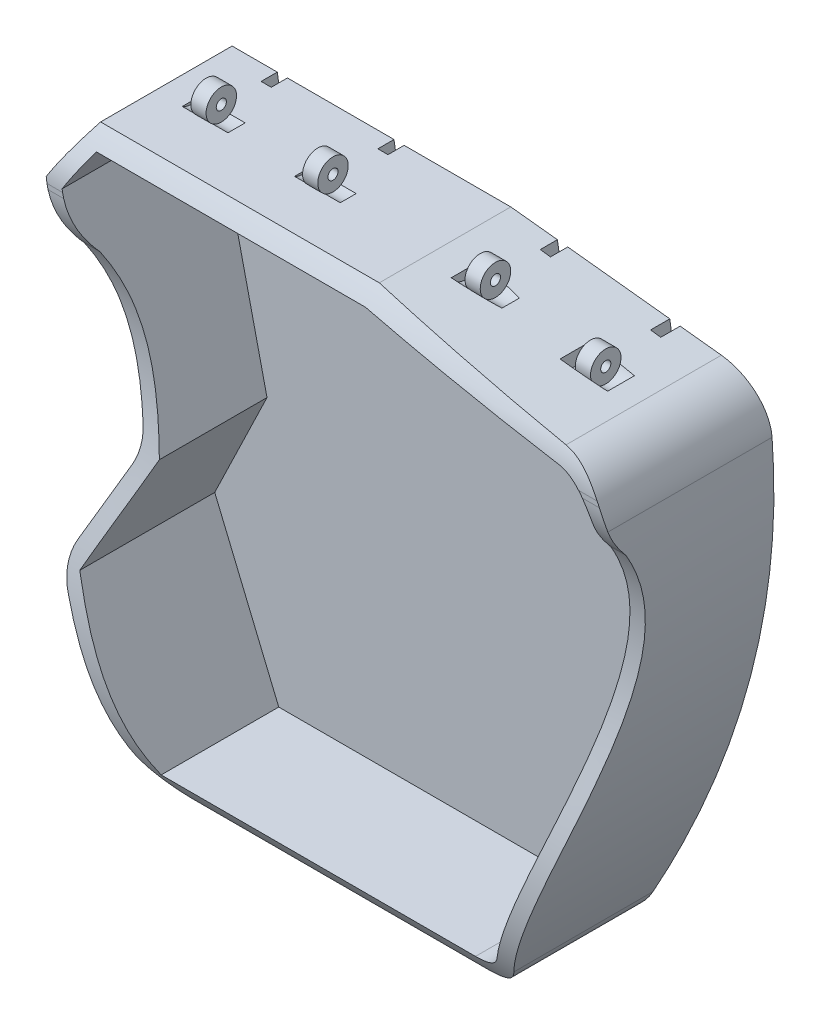
SolidWorks part; units mm, degrees
ref_plane "Front Plane" through (0, 0, 0) normal (0, 0, 1) x (1, 0, 0)
ref_plane "Top Plane" through (0, 0, 0) normal (0, 1, 0) x (1, 0, 0)
ref_plane "Right Plane" through (0, 0, 0) normal (1, 0, 0) x (0, 0, -1)
sketch "Sketch1" plane through (0, 0, 0) normal (0, 0, 1) x (1, 0, 0)
  line L1 (-55, -55) -> (55, -55)
  line L2 (-55, -55) -> (-55, 55)
  line L3 (-55, 55) -> (55, 55)
  line L4 (55, -55) -> (55, 55)
  line L5 (-55, -55) -> (55, 55) construction
  line L6 (-55, 55) -> (55, -55) construction
  point P0 (0, 0)
  dimension "D1" = 110
  dimension "D2" = 110
extrude "Boss-Extrude1" add sketch "Sketch1" along normal mid plane 40
sketch "Sketch2" plane through (0, 0, 20) normal (0, 0, 1) x (1, 0, 0)
  line L0 (-41.1067, -55) -> (-55, -21.5906)
  line L1 (-55, 55) -> (-55, -55) construction
  line L2 (55, 55) -> (-55, 55) construction
  line L3 (-44.5757, 55) -> (5.4243, 55)
  line L4 (-55, -21.5906) -> (-44.5757, 0)
  line L5 (-44.5757, 0) -> (-55, 45.5267)
  line L6 (55, -55) -> (55, 55) construction
  line L7 (-55, -55) -> (55, -55) construction
  line L8 (-44.5757, 55) -> (-49.4797, 55)
  line L9 (-49.4797, 55) -> (-55, 45.5267)
  line L10 (5.4243, 55) -> (55, 48.5)
  spline S0 degree 2 poles (55, 48.5) (55, -6.4605) (28.8836, -55) knots 0 0 0 1 1 1
  point P19 (-41.1067, 5.6448)
  point P20 (-55, 0)
  dimension "D6" = 50
  dimension "D3" = 50
  dimension "D4" = 6.5
extrude "Cut-Extrude1" cut sketch "Sketch2" against normal through all both and the other way through all
ref_plane "Plane1" through (0, 0, -20) normal (0, 0, 1) x (1, 0, 0)
fillet "Fillet1" radius 10 2 edges at (28.8836, -55, 0) (55, 48.5, 0)
sketch "Sketch34" plane through (0, 0, 20) normal (0, 0, 1) x (1, 0, 0)
  line L14 (-39.1052, -52) -> (22.8183, -52)
  line L15 (45.7352, 46.6891) -> (5.2285, 52)
  line L16 (5.2285, 52) -> (-47.7557, 52)
  line L17 (-47.7557, 52) -> (-51.8111, 45.0406)
  line L18 (-51.8111, 45.0406) -> (-41.4164, -0.3565)
  line L19 (-41.4164, -0.3565) -> (-51.7129, -21.6822)
  line L20 (-51.7129, -21.6822) -> (-39.1052, -52)
  line L21 (-39.1052, -52) -> (22.8183, -52)
  line L22 (45.7352, 46.6891) -> (5.2285, 52)
  line L23 (5.2285, 52) -> (-47.7557, 52)
  line L24 (-47.7557, 52) -> (-51.8111, 45.0406)
  line L25 (-51.8111, 45.0406) -> (-41.4164, -0.3565)
  line L26 (-41.4164, -0.3565) -> (-51.7129, -21.6822)
  line L27 (-51.7129, -21.6822) -> (-39.1052, -52)
  arc A4 (22.8183, -52) -> (29.0695, -48.15) centre (22.8183, -45) ccw
  arc A5 (51.8196, 39.4676) -> (45.7352, 46.6891) centre (44.8252, 39.7485) ccw
  arc A6 (22.8183, -52) -> (29.0695, -48.15) centre (22.8183, -45) ccw
  arc A7 (51.8196, 39.4676) -> (45.7352, 46.6891) centre (44.8252, 39.7485) ccw
  spline S0 degree 3 poles (-3904.7286, -573.1485) (-2467.861, -421.0759) (-98.4263, -556.5702) (47.0636, 1.6142) (48.5776, 9.0491) (49.9702, 18.497) (50.224, 20.3961) (50.68, 24.1989) (50.8823, 26.1025) (105.7114, 616.4777) (-2256.861, 1408.0002) (2334.2829, 1615.3931) knots -18.329353 -18.329353 -18.329353 -18.329353 0.5 0.5 0.75 0.75 0.8125 0.8125 0.875 0.875 20.174807 20.174807 20.174807 20.174807 only from (29.0695, -48.15) to (51.8196, 39.4676)
  spline S1 degree 3 poles (29.0695, -48.15) (35.9622, -34.4718) (41.3444, -20.3278) (47.0636, 1.6142) (48.5776, 9.0491) (49.9702, 18.497) (50.224, 20.3961) (50.68, 24.1989) (51.287, 29.9096) (51.6658, 35.6394) (51.8196, 39.4676) knots 0 0 0 0 0.5 0.5 0.75 0.75 0.8125 0.8125 0.875 1 1 1 1
  dimension "D1" = 3
extrude "Cut-Extrude18" cut sketch "Sketch34" against normal blind 30
sketch "Sketch3" plane through (0, 0, 0) normal (1, 0, 0) x (0, 0, -1)
  line L0 (9.8258, 63.2681) -> (27.0619, 63.2681)
  line L1 (27.0619, 63.2681) -> (27.0619, -62.3212)
  line L2 (27.0619, -62.3212) -> (11.0995, -62.3212)
  line L4 (-14.7201, 55) -> (-14.7201, 63.2681)
  line L5 (-14.7201, 63.2681) -> (-35.1683, 63.2681)
  line L6 (-35.1683, 63.2681) -> (-35.1683, -64.091)
  line L7 (-35.1683, -64.091) -> (-1.2006, -64.091)
  line L8 (-1.2006, -64.091) -> (-10.8074, -55.445)
  line L12 (-20, 55) -> (20, 55) construction
  line L13 (-20, 49.6636) -> (-20, 39.3472) construction
  spline S0 degree 2 poles (9.8258, 63.2681) (20.8245, 0.5714) (11.0995, -62.3212) knots 0 0 0 1 1 1
  spline S1 degree 2 poles (-14.7201, 55) (-25.0524, 44.4525) (-15.2012, 33.2765) knots 0 0 0 1 1 1
  spline S2 degree 3 poles (-15.2012, 33.2765) (3.7139, 2.8075) (-32.6776, -26.7515) (-10.8074, -55.445) knots 0 0 0 0 1 1 1 1
extrude "Cut-Extrude2" cut sketch "Sketch3" against normal through all both and the other way through all
ref_plane "Plane2" through (0, 0, -20) normal (0, 0, 1) x (1, 0, 0)
sketch "Sketch5" plane through (0, 0, -20) normal (0, 0, 1) x (1, 0, 0)
  line L0 (5.4243, 61.4359) -> (5.4243, 19.0331) construction
  line L1 (16.4243, 39.4691) -> (14.4243, 39.4691)
  line L4 (-16.5847, 61.4118) -> (-16.5847, 19.009) construction
  line L6 (-39.5796, 61.4359) -> (-39.5796, 19.0331) construction
  line L8 (-40.5796, 39.4932) -> (-38.5796, 39.4932)
  line L10 (-17.5847, 39.4691) -> (-15.5847, 39.4691)
  line L13 (-40.5796, 39.4932) -> (-40.5796, 65.1854)
  line L14 (-40.5796, 65.1854) -> (-38.5796, 65.1854)
  line L15 (-38.5796, 65.1854) -> (-38.5796, 39.4932)
  line L16 (-17.5847, 39.4691) -> (-17.5847, 65.1613)
  line L17 (-17.5847, 65.1613) -> (-15.5847, 65.1613)
  line L18 (-15.5847, 65.1613) -> (-15.5847, 39.4691)
  line L19 (15.4243, 61.4359) -> (15.4243, 19.0331) construction
  line L28 (14.4243, 39.4691) -> (14.4243, 65.1613)
  line L29 (25.4243, 56.3576) -> (25.4243, 38.1329) construction
  line L30 (28.1543, 61.4359) -> (28.1543, 19.0331) construction
  line L31 (16.4243, 39.4691) -> (16.4243, 65.1613)
  line L32 (37.1543, 63.1513) -> (37.1543, 19.0331) construction
  line L33 (14.4243, 65.1613) -> (16.4243, 65.1613)
  line L34 (38.1543, 41.0922) -> (36.1543, 41.0922)
  line L35 (36.1543, 41.0922) -> (36.1543, 65.1613)
  line L36 (38.1543, 41.0922) -> (38.1543, 65.1613)
  line L37 (36.1543, 65.1613) -> (38.1543, 65.1613)
  point P6 (15.4243, 39.4691)
  point P14 (69.1811, 21.2149)
  point P15 (-29.5796, 43.7093)
  point P16 (-26.5847, 43.8832)
  point P20 (-39.5796, 39.4932)
  point P33 (-16.5847, 39.4691)
  point P36 (37.1543, 41.0922)
  dimension "D12" = 1
  dimension "D1" = 10
  dimension "D3" = 1
  dimension "D4" = 1
  dimension "D5" = 10
  dimension "D6" = 3
  dimension "D7" = 2.73
  dimension "D8" = 10
  dimension "D9" = 10
  dimension "D10" = 9
  dimension "D11" = 1
extrude "Cut-Extrude3" cut sketch "Sketch5" along normal blind 12
ref_plane "Plane3" through (37.1543, 0, 0) normal (-1, 0, 0) x (0, 0, 1)
sketch "Sketch6" plane through (37.1543, 0, 0) normal (-1, 0, 0) x (0, 0, 1)
  line L0 (3.3341, 49.6636) -> (3.3341, 61.377) construction
  line L1 (18.6363, 49.6636) -> (-11.9682, 49.6636) construction
  circle A1 centre (3.3341, 51.6636) radius 3
  dimension "D1" = 6
  dimension "D2" = 2
extrude "Boss-Extrude2" add sketch "Sketch6" along normal mid plane 3
sketch "Sketch7" plane through (38.6543, 0, 0) normal (1, 0, 0) x (0, 0, -1)
  circle A0 centre (-3.3341, 51.6636) radius 3
extrude "Cut-Extrude4" cut sketch "Sketch7" along normal blind 3
mirror "Mirror1" about plane through (37.1543, 0, 0) normal (-1, 0, 0) of "Cut-Extrude4"
sketch "Sketch8" plane through (38.6543, 0, 0) normal (1, 0, 0) x (0, 0, -1)
  circle A0 centre (-3.3341, 51.6636) radius 1
  dimension "D1" = 2
extrude "Cut-Extrude5" cut sketch "Sketch8" against normal blind 3
ref_plane "Plane4" through (15.4243, 0, 0) normal (-1, 0, 0) x (0, 0, 1)
sketch "Sketch9" plane through (15.4243, 0, 0) normal (-1, 0, 0) x (0, 0, 1)
  line L0 (3.3341, 49.6636) -> (3.3341, 61.6243) construction
  line L1 (18.6363, 49.6636) -> (-11.9682, 49.6636) construction
  circle A0 centre (3.3341, 55.5578) radius 3
  dimension "D1" = 6
  dimension "D2" = 2
extrude "Boss-Extrude3" add sketch "Sketch9" along normal mid plane 3
sketch "Sketch10" plane through (16.9243, 0, 0) normal (1, 0, 0) x (0, 0, -1)
  circle A0 centre (-3.3341, 55.5578) radius 3
extrude "Cut-Extrude6" cut sketch "Sketch10" along normal blind 3
mirror "Mirror2" about plane through (15.4243, 0, 0) normal (-1, 0, 0) of "Cut-Extrude6"
sketch "Sketch11" plane through (16.9243, 0, 0) normal (1, 0, 0) x (0, 0, -1)
  circle A0 centre (-3.3341, 55.5578) radius 1
  dimension "D1" = 2
extrude "Cut-Extrude7" cut sketch "Sketch11" against normal blind 3
ref_plane "Plane5" through (-16.5847, 0, 0) normal (-1, 0, 0) x (0, 0, 1)
sketch "Sketch12" plane through (-16.5847, 0, 0) normal (-1, 0, 0) x (0, 0, 1)
  line L0 (3.3341, 55.5578) -> (3.3341, 66.3589) construction
  circle A1 centre (3.3341, 57.5578) radius 3
  point P1 (-8.001, 54.9995)
  dimension "D1" = 6
  dimension "D2" = 2
extrude "Boss-Extrude4" add sketch "Sketch12" along normal mid plane 3
sketch "Sketch13" plane through (-15.0847, 0, 0) normal (1, 0, 0) x (0, 0, -1)
  circle A0 centre (-3.3341, 57.5578) radius 3
extrude "Cut-Extrude8" cut sketch "Sketch13" along normal blind 3
mirror "Mirror3" about plane through (-16.5847, 0, 0) normal (-1, 0, 0) of "Cut-Extrude8"
sketch "Sketch14" plane through (-15.0847, 0, 0) normal (1, 0, 0) x (0, 0, -1)
  circle A0 centre (-3.3341, 57.5578) radius 1
  dimension "D1" = 2
extrude "Cut-Extrude9" cut sketch "Sketch14" against normal blind 3
ref_plane "Plane6" through (-39.5796, 0, 0) normal (-1, 0, 0) x (0, 0, 1)
sketch "Sketch15" plane through (-39.5796, 0, 0) normal (-1, 0, 0) x (0, 0, 1)
  line L0 (2.3375, 55.4744) -> (2.3375, 64.0776) construction
  circle A0 centre (3.3341, 55.5578) radius 1 construction
  circle A1 centre (2.3375, 57.4744) radius 3
  dimension "D1" = 6
  dimension "D2" = 2
extrude "Boss-Extrude5" add sketch "Sketch15" along normal mid plane 3
sketch "Sketch16" plane through (-41.0796, 0, 0) normal (-1, 0, 0) x (0, 0, 1)
  circle A0 centre (2.3375, 57.4744) radius 3
extrude "Cut-Extrude10" cut sketch "Sketch16" along normal blind 3
mirror "Mirror4" about plane through (-39.5796, 0, 0) normal (-1, 0, 0) of "Cut-Extrude10"
sketch "Sketch17" plane through (-41.0796, 0, 0) normal (-1, 0, 0) x (0, 0, 1)
  circle A0 centre (2.3375, 57.4744) radius 1
  dimension "D1" = 2
extrude "Cut-Extrude11" cut sketch "Sketch17" against normal blind 3
fillet "Fillet7" radius 10 3 edges at (-41.1067, -55, -0.5098) (-55, -21.5906, 0.6732) (-44.5757, 0, -2.2593)
sketch "Sketch35" plane through (7.181, 54.7697, 0) normal (0.13, 0.9915, 0) x (0.9915, -0.13, 0)
  line L0 (30.2298, 8) -> (30.2298, -17.9958) construction
  line L1 (31.2384, 8) -> (29.2213, 8) construction
  line L2 (8.3139, 8) -> (8.3139, -15.9244) construction
  line L3 (7.3053, 8) -> (9.3224, 8) construction
  spline S0 degree 3 poles (39.2775, -18.6363) (25.5569, -17.7592) (11.8668, -16.4569) (-1.7717, -14.7201) knots 0 0 0 0 1 1 1 1 construction
